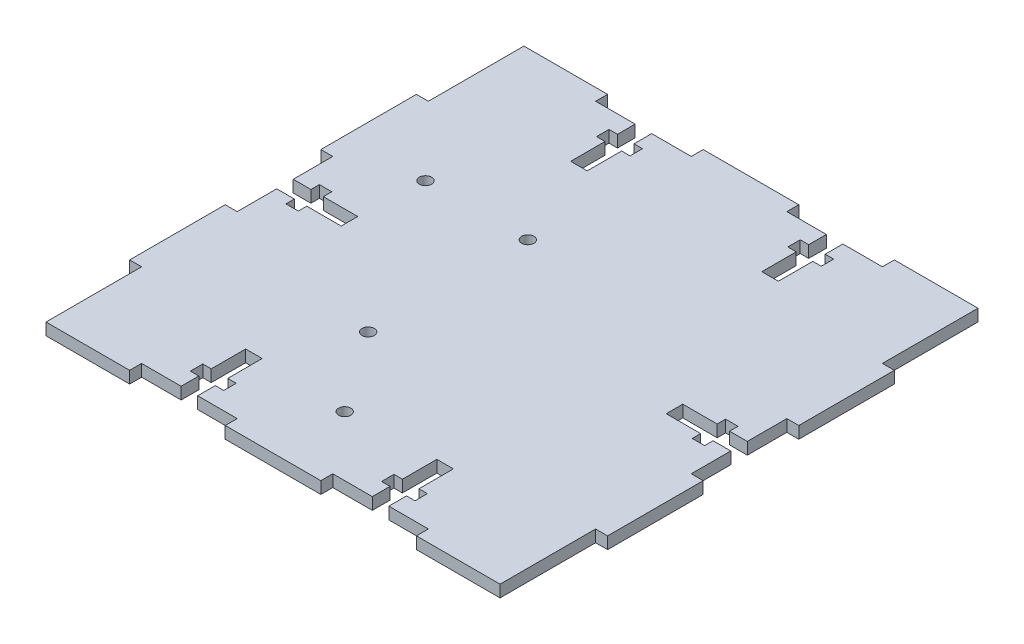
SolidWorks part; units mm, degrees
ref_plane "Front Plane" through (0, 0, 0) normal (0, 0, 1) x (1, 0, 0)
ref_plane "Top Plane" through (0, 0, 0) normal (0, 1, 0) x (1, 0, 0)
ref_plane "Right Plane" through (0, 0, 0) normal (1, 0, 0) x (0, 0, -1)
sketch "Sketch1" plane through (0, 0, 0) normal (0, 1, 0) x (1, 0, 0)
  line L1 (0, 0) -> (127, 0)
  line L2 (0, 0) -> (0, 127)
  line L3 (0, 127) -> (127, 127)
  line L4 (127, 0) -> (127, 127)
  dimension "D1" = 127
  dimension "D2" = 127
extrude "Boss-Extrude1" add sketch "Sketch1" along normal blind 3.175
sketch "Sketch2" plane through (0, 3.175, 0) normal (0, 1, 0) x (1, 0, 0)
  line L1 (0, 127) -> (3.175, 127)
  line L2 (0, 127) -> (0, 101.6)
  line L3 (0, 101.6) -> (3.175, 101.6)
  line L4 (3.175, 127) -> (3.175, 101.6)
  dimension "D1" = 25.4
  dimension "D2" = 3.175
extrude "Cut-Extrude1" cut sketch "Sketch2" against normal blind 6.35
pattern_linear "LPattern1" count 3 spacing 50.8 along (0, 0, 1) count 2 spacing 123.825 along (1, 0, 0) of "Cut-Extrude1"
sketch "Sketch3" plane through (0, 3.175, 0) normal (0, 1, 0) x (1, 0, 0)
  line L0 (3.175, 0) -> (123.825, 0) construction
  line L1 (25.4, 0) -> (50.8, 0)
  line L2 (25.4, 0) -> (25.4, 3.175)
  line L3 (25.4, 3.175) -> (50.8, 3.175)
  line L4 (50.8, 0) -> (50.8, 3.175)
  line L5 (0, 50.8) -> (0, 25.4) construction
  dimension "D1" = 25.4
  dimension "D2" = 3.175
  dimension "D3" = 25.4
extrude "Cut-Extrude2" cut sketch "Sketch3" against normal blind 6.35
pattern_linear "LPattern2" count 3 spacing 50.8 along (1, 0, 0) count 2 spacing 123.825 along (0, 0, -1) of "Cut-Extrude2"
ref_plane "Plane1" through (0, 0, -63.5) normal (0, 0, 1) x (1, 0, 0)
sketch "Sketch4" plane through (0, 3.175, 0) normal (0, 1, 0) x (1, 0, 0)
  line L0 (123.825, 76.2) -> (123.825, 50.8) construction
  line L1 (123.825, 65.6971) -> (106.68, 65.6971)
  line L2 (123.825, 65.6971) -> (123.825, 61.3029)
  line L3 (123.825, 61.3029) -> (106.68, 61.3029)
  line L4 (106.68, 65.6971) -> (106.68, 61.3029)
  line L5 (127, 76.2) -> (123.825, 76.2) construction
  line L7 (115.824, 67.945) -> (119.126, 67.945)
  line L8 (115.824, 67.945) -> (115.824, 59.055)
  line L9 (115.824, 59.055) -> (119.126, 59.055)
  line L10 (119.126, 67.945) -> (119.126, 59.055)
  point P6 (123.825, 63.5)
  point P13 (117.475, 59.055)
  point P14 (119.126, 63.5)
  dimension "D1" = 17.145
  dimension "D2" = 4.3942
  dimension "D3" = 12.7
  dimension "D4" = 3.302
  dimension "D5" = 6.35
  dimension "D6" = 8.89
  dimension "D7" = 12.7
extrude "Cut-Extrude3" cut sketch "Sketch4" against normal blind 8.89 contours L1 L4 L3 L2 | L7 L10 L9 L8
sketch "Sketch5" plane through (0, 3.175, 0) normal (0, 1, 0) x (1, 0, 0)
  line L0 (50.8, 3.175) -> (25.4, 3.175) construction
  line L1 (35.9029, 3.175) -> (40.2971, 3.175)
  line L2 (35.9029, 3.175) -> (35.9029, 20.32)
  line L3 (35.9029, 20.32) -> (40.2971, 20.32)
  line L4 (40.2971, 3.175) -> (40.2971, 20.32)
  line L5 (50.8, 0) -> (50.8, 3.175) construction
  line L6 (33.655, 11.176) -> (42.545, 11.176)
  line L7 (33.655, 11.176) -> (33.655, 7.874)
  line L8 (33.655, 7.874) -> (42.545, 7.874)
  line L9 (42.545, 11.176) -> (42.545, 7.874)
  point P6 (38.1, 20.32)
  point P12 (38.1, 7.874)
  point P15 (42.545, 9.525)
  dimension "D1" = 17.145
  dimension "D2" = 4.3942
  dimension "D3" = 12.7
  dimension "D4" = 3.302
  dimension "D5" = 8.89
  dimension "D6" = 12.7
  dimension "D7" = 6.35
extrude "Cut-Extrude4" cut sketch "Sketch5" against normal blind 30.48 contours L3 L4 L1 L2 | L7 L8 L9 L6
pattern_linear "LPattern3" count 2 spacing 50.8 along (1, 0, 0) of "Cut-Extrude4"
sketch "Sketch10" plane through (0, 3.175, 0) normal (0, 1, 0) x (1, 0, 0)
  line L1 (78.7908, 104.775) -> (101.6, 104.775)
  line L2 (78.7908, 104.775) -> (78.7908, 48.8442)
  line L3 (78.7908, 48.8442) -> (101.6, 48.8442)
  line L4 (101.6, 104.775) -> (101.6, 48.8442)
  line L5 (76.2, 123.825) -> (101.6, 123.825) construction
  line L6 (127, 76.2) -> (127, 101.6) construction
  dimension "D1" = 22.8092
  dimension "D2" = 55.9308
  dimension "D3" = 25.4
  dimension "D4" = 19.05
mirror "Mirror2" about plane through (0, 0, -63.5) normal (0, 0, 1) of "LPattern3", "Cut-Extrude4"
sketch "2x2_PCB" plane through (0, 3.175, 0) normal (0, 1, 0) x (1, 0, 0)
  line L0 (106.68, 65.6971) -> (106.68, 61.3029) construction
  line L1 (10.16, 90.551) -> (60.96, 90.551)
  line L2 (10.16, 90.551) -> (10.16, 36.449)
  line L3 (10.16, 36.449) -> (60.96, 36.449)
  line L4 (60.96, 90.551) -> (60.96, 36.449)
  line L5 (10.16, 90.551) -> (60.96, 36.449) construction
  line L6 (10.16, 36.449) -> (60.96, 90.551) construction
  line L8 (0, 101.6) -> (0, 76.2) construction
  point P0 (35.56, 63.5)
  point P7 (106.68, 63.5)
  point P8 (35.56, 90.551)
  dimension "D1" = 50.8
  dimension "D2" = 54.102
  dimension "D3" = 35.56
hole_wizard "#4 Clearance Hole3" positions "Sketch15" profile "Sketch14" hole size "#4" standard "ANSI Inch"
sketch "Sketch15" plane through (0, 3.175, 0) normal (0, 1, 0) x (1, 0, 0)
  line L0 (10.16, 90.551) -> (60.96, 90.551) construction
  line L3 (10.16, 90.551) -> (10.16, 36.449) construction
  point P0 (21.082, 82.931)
  point P2 (48.26, 82.931)
  point P4 (48.26, 40.513)
  dimension "D1" = 7.62
  dimension "D2" = 10.922
  dimension "D3" = 27.178
  dimension "D4" = 42.418
sketch "Sketch14" plane through (21.082, 3.175, -82.931) normal (1, 0, 0) x (0, 0, 1)
  line L0 (0, 0) -> (0, 11.1406)
  line L1 (0, 11.1406) -> (1.6319, 10.16)
  line L2 (1.6319, 10.16) -> (1.6319, 0)
  line L5 (1.6319, 0) -> (0, 0)
  line L10 (0, 11.1406) -> (-1.632, 10.16) construction
  line L11 (0, -6.35) -> (0, 107.95) construction
  dimension "Hole Dia." = 3.2639
  dimension "Hole Depth" = 10.16
  dimension "Drill Angle" = 118
hole_wizard "#4 Clearance Hole4" positions "Sketch18" profile "Sketch16" hole size "#4" standard "ANSI Inch"
sketch "Sketch18" plane through (0, 3.175, 0) normal (0, 1, 0) x (1, 0, 0)
  line L0 (127, 25.4) -> (127, 50.8) construction
  line L2 (50.8, 0) -> (76.2, 0) construction
  point P0 (63.5, 19.05)
  dimension "D1" = 63.5
  dimension "D2" = 19.05
sketch "Sketch16" plane through (63.5, 3.175, -19.05) normal (1, 0, 0) x (0, 0, 1)
  line L0 (0, 0) -> (0, 11.1406)
  line L1 (0, 11.1406) -> (1.6319, 10.16)
  line L2 (1.6319, 10.16) -> (1.6319, 0)
  line L5 (1.6319, 0) -> (0, 0)
  line L10 (0, 11.1406) -> (-1.632, 10.16) construction
  line L11 (0, -6.35) -> (0, 107.95) construction
  dimension "Hole Dia." = 3.2639
  dimension "Hole Depth" = 10.16
  dimension "Drill Angle" = 118
ref_plane "Plane2" through (63.5, 0, 0) normal (-1, 0, 0) x (0, 0, 1)
mirror "Mirror3" about plane through (63.5, 0, 0) normal (-1, 0, 0) of "Cut-Extrude3"
